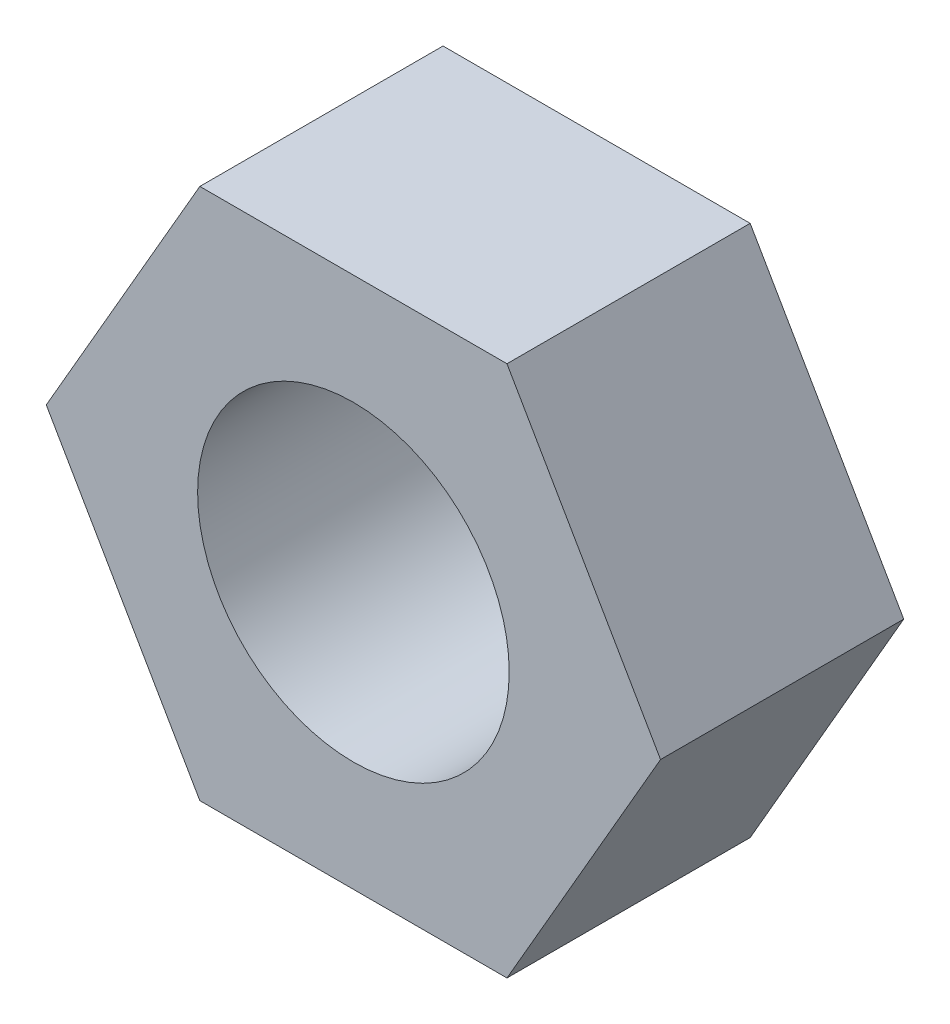
SolidWorks part; units mm, degrees
ref_plane "Спереди" through (0, 0, 0) normal (0, 0, 1) x (1, 0, 0)
ref_plane "Сверху" through (0, 0, 0) normal (0, 1, 0) x (1, 0, 0)
ref_plane "Справа" through (0, 0, 0) normal (1, 0, 0) x (0, 0, -1)
sketch "Эскиз1" plane through (0, 0, 0) normal (0, 0, 1) x (1, 0, 0)
  line L1 (4.0415, 0) -> (2.0207, 3.5)
  line L2 (2.0207, 3.5) -> (-2.0207, 3.5)
  line L3 (-2.0207, 3.5) -> (-4.0415, 0)
  line L4 (-4.0415, 0) -> (-2.0207, -3.5)
  line L5 (-2.0207, -3.5) -> (2.0207, -3.5)
  line L6 (2.0207, -3.5) -> (4.0415, 0)
  circle A0 centre (0, 0) radius 3.5 construction
  dimension "D1" = 7
extrude "Бобышка-Вытянуть1" add sketch "Эскиз1" along normal blind 3.2
sketch "Эскиз2" plane through (0, 0, 3.2) normal (0, 0, 1) x (1, 0, 0)
  circle A0 centre (0, 0) radius 2.05
  dimension "D1" = 4.1
extrude "Вырез-Вытянуть1" cut sketch "Эскиз2" against normal through all
